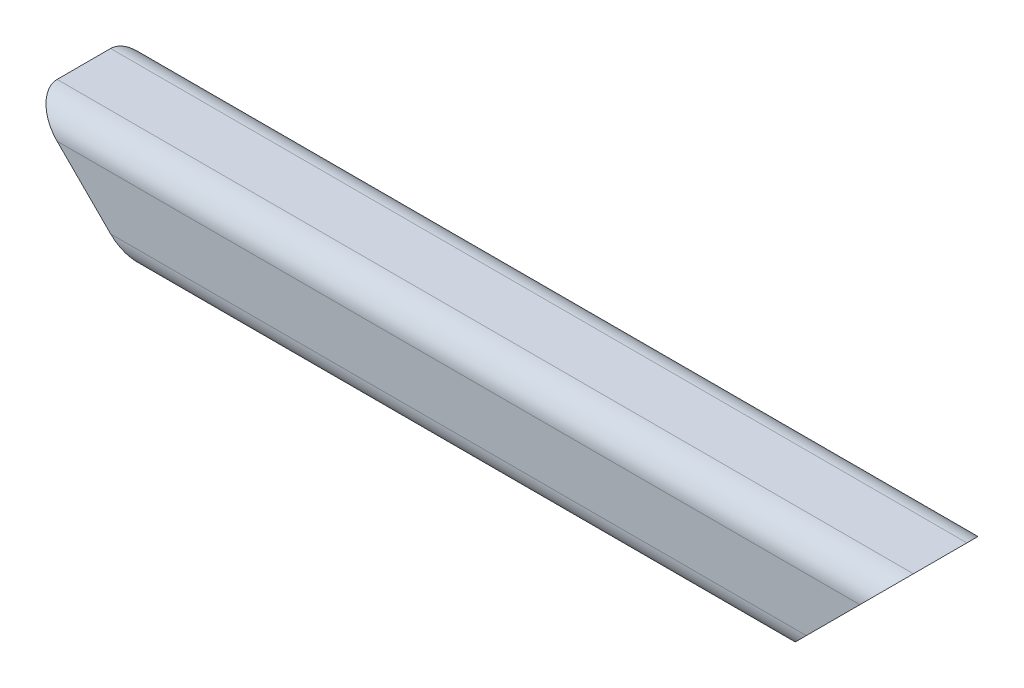
SolidWorks part; units mm, degrees
material "Plain Carbon Steel"
ref_plane "Front Plane" through (0, 0, 0) normal (0, 0, 1) x (1, 0, 0)
ref_plane "Top Plane" through (0, 0, 0) normal (0, 1, 0) x (1, 0, 0)
ref_plane "Right Plane" through (0, 0, 0) normal (1, 0, 0) x (0, 0, -1)
sketch3d "3DSketch1"
  line L0 (0, 0, 0) -> (-406.4, 0, 0)
  dimension "D1" = 406.4
other "Structural Member1"
ref_plane "Plane1" through (0, 0, 0) normal (-1, 0, 0) x (0, 0, 1)
sketch "Sketch11" plane through (0, 0, 0) normal (-1, 0, 0) x (0, 0, 1)
  line L0 (-12.7, -22.225) -> (12.7, -22.225)
  line L1 (-22.225, -12.7) -> (-22.225, 12.7)
  line L2 (12.7, 22.225) -> (-12.7, 22.225)
  line L3 (22.225, 12.7) -> (22.225, -12.7)
  line L4 (-12.7, -25.4) -> (12.7, -25.4)
  line L5 (-25.4, -12.7) -> (-25.4, 12.7)
  line L6 (12.7, 25.4) -> (-12.7, 25.4)
  line L7 (25.4, 12.7) -> (25.4, -12.7)
  line L8 (0, 0) -> (22.225, 0) construction
  line L9 (0, 0) -> (0, 22.225) construction
  arc A0 (25.4, 12.7) -> (12.7, 25.4) centre (12.7, 12.7) ccw
  arc A1 (12.7, -25.4) -> (25.4, -12.7) centre (12.7, -12.7) ccw
  arc A2 (-25.4, -12.7) -> (-12.7, -25.4) centre (-12.7, -12.7) ccw
  arc A3 (-12.7, 25.4) -> (-25.4, 12.7) centre (-12.7, 12.7) ccw
  arc A4 (-12.7, 22.225) -> (-22.225, 12.7) centre (-12.7, 12.7) ccw
  arc A5 (22.225, 12.7) -> (12.7, 22.225) centre (12.7, 12.7) ccw
  arc A6 (12.7, -22.225) -> (22.225, -12.7) centre (12.7, -12.7) ccw
  arc A7 (-22.225, -12.7) -> (-12.7, -22.225) centre (-12.7, -12.7) ccw
  point P3 (0, 25.4)
  point P4 (25.4, 0)
  point P5 (0, -25.4)
  point P6 (-25.4, 0)
  point P7 (-25.4, 25.4)
  point P8 (-25.4, -25.4)
  point P33 (0, 0)
  point P35 (25.4, -25.4)
  point P36 (25.4, 25.4)
  point P37 (0, 0)
  dimension "D1" = 12.7
  dimension "Thickness" = 3.175
  dimension "V_leg" = 50.8
sketch "Sketch2" plane through (0, 0, 25.4) normal (0, 0, 1) x (1, 0, 0)
  line L0 (-406.4, 25.4) -> (-355.6, -25.4)
  line L1 (-406.4, -25.4) -> (0, -25.4) construction
  line L2 (-355.6, -25.4) -> (-406.4, -25.4)
  line L3 (-406.4, -25.4) -> (-406.4, 25.4)
  line L4 (0, 25.4) -> (-50.8, -25.4)
  line L7 (0, 25.4) -> (0, -25.4)
  line L8 (-50.8, -25.4) -> (0, -25.4)
extrude "Cut-Extrude1" cut sketch "Sketch2" against normal through all
